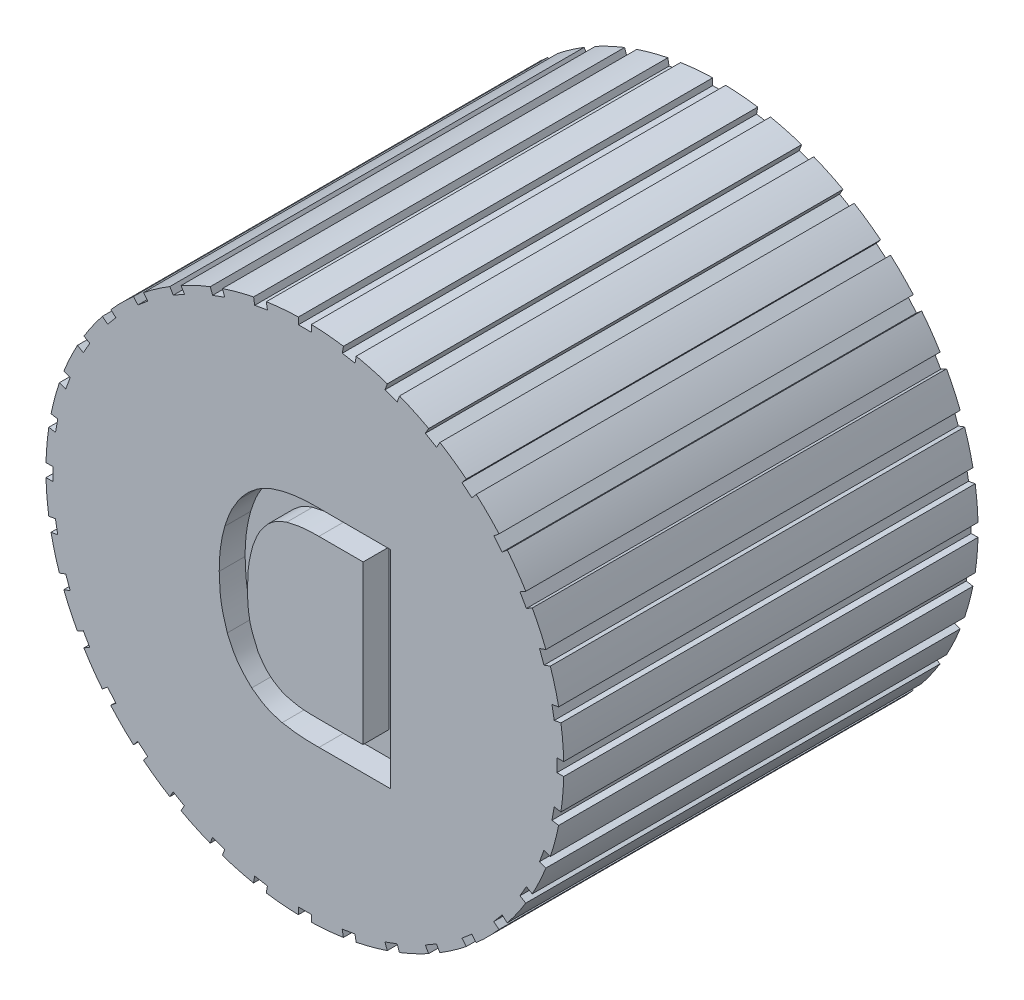
SolidWorks part; units mm, degrees
ref_plane "Front Plane" through (0, 0, 0) normal (0, 0, 1) x (1, 0, 0)
ref_plane "Top Plane" through (0, 0, 0) normal (0, 1, 0) x (1, 0, 0)
ref_plane "Right Plane" through (0, 0, 0) normal (1, 0, 0) x (0, 0, -1)
sketch "Sketch1" plane through (0, 0, 0) normal (0, 1, 0) x (1, 0, 0)
  line L0 (10, 0) -> (0, 0)
  line L1 (0, 0) -> (0, -16)
  line L2 (0, -16) -> (10, -16)
  line L3 (10, -16) -> (10, 0)
  line L4 (0, 0) -> (0, -16) construction
revolve "Revolve1" add sketch "Sketch1" angle 360 about L4
sketch "Sketch2" plane through (0, 0, 0) normal (0, 0, -1) x (-1, 0, 0)
  line L0 (3.183, 9.4799) -> (3.0936, 9.2344)
  line L1 (3.0936, 9.2344) -> (3.5632, 9.0635)
  line L2 (3.5632, 9.0635) -> (3.6526, 9.3091)
  arc A0 (3.6526, 9.3091) -> (3.183, 9.4799) centre (0, 0) ccw
extrude "Cut-Extrude1" cut sketch "Sketch2" against normal blind 16
sketch "Sketch3" plane through (0, 0, 0) normal (0, 0, -1) x (-1, 0, 0)
  line L0 (4.7808, 8.7832) -> (4.6502, 8.5569)
  line L1 (4.6502, 8.5569) -> (5.0829, 8.307)
  line L2 (5.0829, 8.307) -> (5.2136, 8.5334)
  arc A0 (5.2136, 8.5334) -> (4.7808, 8.7832) centre (0, 0) ccw
extrude "Cut-Extrude2" cut sketch "Sketch3" against normal blind 16
sketch "Sketch4" plane through (0, 0, 0) normal (0, 0, -1) x (-1, 0, 0)
  line L0 (6.2334, 7.8195) -> (6.0654, 7.6194)
  line L1 (6.0654, 7.6194) -> (6.4482, 7.2982)
  line L2 (6.4482, 7.2982) -> (6.6162, 7.4984)
  arc A0 (6.6162, 7.4984) -> (6.2334, 7.8195) centre (0, 0) ccw
extrude "Cut-Extrude3" cut sketch "Sketch4" against normal blind 16
sketch "Sketch5" plane through (0, 0, 0) normal (0, 0, -1) x (-1, 0, 0)
  line L0 (7.4965, 6.6183) -> (7.2963, 6.4504)
  line L1 (7.2963, 6.4504) -> (7.6176, 6.0676)
  line L2 (7.6176, 6.0676) -> (7.8178, 6.2356)
  arc A0 (7.8178, 6.2356) -> (7.4965, 6.6183) centre (0, 0) ccw
extrude "Cut-Extrude4" cut sketch "Sketch5" against normal blind 16
sketch "Sketch6" plane through (0, 0, 0) normal (0, 0, -1) x (-1, 0, 0)
  line L0 (8.5319, 5.216) -> (8.3056, 5.0854)
  line L1 (8.3056, 5.0854) -> (8.5554, 4.6526)
  line L2 (8.5554, 4.6526) -> (8.7818, 4.7833)
  arc A0 (8.7818, 4.7833) -> (8.5319, 5.216) centre (0, 0) ccw
extrude "Cut-Extrude5" cut sketch "Sketch6" against normal blind 16
sketch "Sketch7" plane through (0, 0, 0) normal (0, 0, -1) x (-1, 0, 0)
  line L0 (9.308, 3.6552) -> (9.0625, 3.5659)
  line L1 (9.0625, 3.5659) -> (9.2334, 3.0963)
  line L2 (9.2334, 3.0963) -> (9.479, 3.1857)
  arc A0 (9.479, 3.1857) -> (9.308, 3.6552) centre (0, 0) ccw
extrude "Cut-Extrude6" cut sketch "Sketch7" against normal blind 16
sketch "Sketch8" plane through (0, 0, 0) normal (0, 0, -1) x (-1, 0, 0)
  line L0 (9.8013, 1.9834) -> (9.544, 1.938)
  line L1 (9.544, 1.938) -> (9.6308, 1.4459)
  line L2 (9.6308, 1.4459) -> (9.8882, 1.4913)
  arc A0 (9.8882, 1.4913) -> (9.8013, 1.9834) centre (0, 0) ccw
extrude "Cut-Extrude7" cut sketch "Sketch8" against normal blind 16
sketch "Sketch9" plane through (0, 0, 0) normal (0, 0, -1) x (-1, 0, 0)
  line L0 (9.9968, 0.2513) -> (9.7356, 0.2513)
  line L1 (9.7356, 0.2513) -> (9.7356, -0.2484)
  line L2 (9.7356, -0.2484) -> (9.9969, -0.2484)
  arc A0 (9.9969, -0.2484) -> (9.9968, 0.2513) centre (0, 0) ccw
extrude "Cut-Extrude8" cut sketch "Sketch9" against normal blind 16
sketch "Sketch10" plane through (0, 0, 0) normal (0, 0, -1) x (-1, 0, 0)
  line L0 (9.8886, -1.4885) -> (9.6313, -1.4431)
  line L1 (9.6313, -1.4431) -> (9.5445, -1.9352)
  line L2 (9.5445, -1.9352) -> (9.8019, -1.9806)
  arc A0 (9.8019, -1.9806) -> (9.8886, -1.4885) centre (0, 0) ccw
extrude "Cut-Extrude9" cut sketch "Sketch10" against normal blind 16
sketch "Sketch11" plane through (0, 0, 0) normal (0, 0, -1) x (-1, 0, 0)
  line L0 (9.4799, -3.183) -> (9.2344, -3.0936)
  line L1 (9.2344, -3.0936) -> (9.0635, -3.5632)
  line L2 (9.0635, -3.5632) -> (9.3091, -3.6526)
  arc A0 (9.3091, -3.6526) -> (9.4799, -3.183) centre (0, 0) ccw
extrude "Cut-Extrude10" cut sketch "Sketch11" against normal blind 16
sketch "Sketch12" plane through (0, 0, 0) normal (0, 0, -1) x (-1, 0, 0)
  line L0 (8.7832, -4.7808) -> (8.5569, -4.6502)
  line L1 (8.5569, -4.6502) -> (8.307, -5.0829)
  line L2 (8.307, -5.0829) -> (8.5334, -5.2136)
  arc A0 (8.5334, -5.2136) -> (8.7832, -4.7808) centre (0, 0) ccw
extrude "Cut-Extrude11" cut sketch "Sketch12" against normal blind 16
sketch "Sketch13" plane through (0, 0, 0) normal (0, 0, -1) x (-1, 0, 0)
  line L0 (7.8195, -6.2334) -> (7.6194, -6.0654)
  line L1 (7.6194, -6.0654) -> (7.2982, -6.4482)
  line L2 (7.2982, -6.4482) -> (7.4984, -6.6162)
  arc A0 (7.4984, -6.6162) -> (7.8195, -6.2334) centre (0, 0) ccw
extrude "Cut-Extrude12" cut sketch "Sketch13" against normal blind 16
sketch "Sketch14" plane through (0, 0, 0) normal (0, 0, -1) x (-1, 0, 0)
  line L0 (6.6183, -7.4965) -> (6.4504, -7.2963)
  line L1 (6.4504, -7.2963) -> (6.0676, -7.6176)
  line L2 (6.0676, -7.6176) -> (6.2356, -7.8178)
  arc A0 (6.2356, -7.8178) -> (6.6183, -7.4965) centre (0, 0) ccw
extrude "Cut-Extrude13" cut sketch "Sketch14" against normal blind 16
sketch "Sketch15" plane through (0, 0, 0) normal (0, 0, -1) x (-1, 0, 0)
  line L0 (5.216, -8.5319) -> (5.0854, -8.3056)
  line L1 (5.0854, -8.3056) -> (4.6526, -8.5554)
  line L2 (4.6526, -8.5554) -> (4.7833, -8.7818)
  arc A0 (4.7833, -8.7818) -> (5.216, -8.5319) centre (0, 0) ccw
extrude "Cut-Extrude14" cut sketch "Sketch15" against normal blind 16
sketch "Sketch16" plane through (0, 0, 0) normal (0, 0, -1) x (-1, 0, 0)
  line L0 (3.6552, -9.308) -> (3.5659, -9.0625)
  line L1 (3.5659, -9.0625) -> (3.0963, -9.2334)
  line L2 (3.0963, -9.2334) -> (3.1857, -9.479)
  arc A0 (3.1857, -9.479) -> (3.6552, -9.308) centre (0, 0) ccw
extrude "Cut-Extrude15" cut sketch "Sketch16" against normal blind 16
sketch "Sketch17" plane through (0, 0, 0) normal (0, 0, -1) x (-1, 0, 0)
  line L0 (1.9834, -9.8013) -> (1.938, -9.544)
  line L1 (1.938, -9.544) -> (1.4459, -9.6308)
  line L2 (1.4459, -9.6308) -> (1.4913, -9.8882)
  arc A0 (1.4913, -9.8882) -> (1.9834, -9.8013) centre (0, 0) ccw
extrude "Cut-Extrude16" cut sketch "Sketch17" against normal blind 16
sketch "Sketch18" plane through (0, 0, 0) normal (0, 0, -1) x (-1, 0, 0)
  line L0 (0.2513, -9.9968) -> (0.2513, -9.7356)
  line L1 (0.2513, -9.7356) -> (-0.2484, -9.7356)
  line L2 (-0.2484, -9.7356) -> (-0.2484, -9.9969)
  arc A0 (-0.2484, -9.9969) -> (0.2513, -9.9968) centre (0, 0) ccw
extrude "Cut-Extrude17" cut sketch "Sketch18" against normal blind 16
sketch "Sketch19" plane through (0, 0, 0) normal (0, 0, -1) x (-1, 0, 0)
  line L0 (-1.4885, -9.8886) -> (-1.4431, -9.6313)
  line L1 (-1.4431, -9.6313) -> (-1.9352, -9.5445)
  line L2 (-1.9352, -9.5445) -> (-1.9806, -9.8019)
  arc A0 (-1.9806, -9.8019) -> (-1.4885, -9.8886) centre (0, 0) ccw
extrude "Cut-Extrude18" cut sketch "Sketch19" against normal blind 16
sketch "Sketch20" plane through (0, 0, 0) normal (0, 0, -1) x (-1, 0, 0)
  line L0 (-3.183, -9.4799) -> (-3.0936, -9.2344)
  line L1 (-3.0936, -9.2344) -> (-3.5632, -9.0635)
  line L2 (-3.5632, -9.0635) -> (-3.6526, -9.3091)
  arc A0 (-3.6526, -9.3091) -> (-3.183, -9.4799) centre (0, 0) ccw
extrude "Cut-Extrude19" cut sketch "Sketch20" against normal blind 16
sketch "Sketch21" plane through (0, 0, 0) normal (0, 0, -1) x (-1, 0, 0)
  line L0 (-4.7808, -8.7832) -> (-4.6502, -8.5569)
  line L1 (-4.6502, -8.5569) -> (-5.0829, -8.307)
  line L2 (-5.0829, -8.307) -> (-5.2136, -8.5334)
  arc A0 (-5.2136, -8.5334) -> (-4.7808, -8.7832) centre (0, 0) ccw
extrude "Cut-Extrude20" cut sketch "Sketch21" against normal blind 16
sketch "Sketch22" plane through (0, 0, 0) normal (0, 0, -1) x (-1, 0, 0)
  line L0 (-6.2334, -7.8195) -> (-6.0654, -7.6194)
  line L1 (-6.0654, -7.6194) -> (-6.4482, -7.2982)
  line L2 (-6.4482, -7.2982) -> (-6.6162, -7.4984)
  arc A0 (-6.6162, -7.4984) -> (-6.2334, -7.8195) centre (0, 0) ccw
extrude "Cut-Extrude21" cut sketch "Sketch22" against normal blind 16
sketch "Sketch23" plane through (0, 0, 0) normal (0, 0, -1) x (-1, 0, 0)
  line L0 (-7.4965, -6.6183) -> (-7.2963, -6.4504)
  line L1 (-7.2963, -6.4504) -> (-7.6176, -6.0676)
  line L2 (-7.6176, -6.0676) -> (-7.8178, -6.2356)
  arc A0 (-7.8178, -6.2356) -> (-7.4965, -6.6183) centre (0, 0) ccw
extrude "Cut-Extrude22" cut sketch "Sketch23" against normal blind 16
sketch "Sketch24" plane through (0, 0, 0) normal (0, 0, -1) x (-1, 0, 0)
  line L0 (-8.5319, -5.216) -> (-8.3056, -5.0854)
  line L1 (-8.3056, -5.0854) -> (-8.5554, -4.6526)
  line L2 (-8.5554, -4.6526) -> (-8.7818, -4.7833)
  arc A0 (-8.7818, -4.7833) -> (-8.5319, -5.216) centre (0, 0) ccw
extrude "Cut-Extrude23" cut sketch "Sketch24" against normal blind 16
sketch "Sketch25" plane through (0, 0, 0) normal (0, 0, -1) x (-1, 0, 0)
  line L0 (-9.308, -3.6552) -> (-9.0625, -3.5659)
  line L1 (-9.0625, -3.5659) -> (-9.2334, -3.0963)
  line L2 (-9.2334, -3.0963) -> (-9.479, -3.1857)
  arc A0 (-9.479, -3.1857) -> (-9.308, -3.6552) centre (0, 0) ccw
extrude "Cut-Extrude24" cut sketch "Sketch25" against normal blind 16
sketch "Sketch26" plane through (0, 0, 0) normal (0, 0, -1) x (-1, 0, 0)
  line L0 (-9.8013, -1.9834) -> (-9.544, -1.938)
  line L1 (-9.544, -1.938) -> (-9.6308, -1.4459)
  line L2 (-9.6308, -1.4459) -> (-9.8882, -1.4913)
  arc A0 (-9.8882, -1.4913) -> (-9.8013, -1.9834) centre (0, 0) ccw
extrude "Cut-Extrude25" cut sketch "Sketch26" against normal blind 16
sketch "Sketch27" plane through (0, 0, 0) normal (0, 0, -1) x (-1, 0, 0)
  line L0 (-9.9968, -0.2513) -> (-9.7356, -0.2513)
  line L1 (-9.7356, -0.2513) -> (-9.7356, 0.2484)
  line L2 (-9.7356, 0.2484) -> (-9.9969, 0.2484)
  arc A0 (-9.9969, 0.2484) -> (-9.9968, -0.2513) centre (0, 0) ccw
extrude "Cut-Extrude26" cut sketch "Sketch27" against normal blind 16
sketch "Sketch28" plane through (0, 0, 0) normal (0, 0, -1) x (-1, 0, 0)
  line L0 (-9.8886, 1.4885) -> (-9.6313, 1.4431)
  line L1 (-9.6313, 1.4431) -> (-9.5445, 1.9352)
  line L2 (-9.5445, 1.9352) -> (-9.8019, 1.9806)
  arc A0 (-9.8019, 1.9806) -> (-9.8886, 1.4885) centre (0, 0) ccw
extrude "Cut-Extrude27" cut sketch "Sketch28" against normal blind 16
sketch "Sketch29" plane through (0, 0, 0) normal (0, 0, -1) x (-1, 0, 0)
  line L0 (-9.4799, 3.183) -> (-9.2344, 3.0936)
  line L1 (-9.2344, 3.0936) -> (-9.0635, 3.5632)
  line L2 (-9.0635, 3.5632) -> (-9.3091, 3.6526)
  arc A0 (-9.3091, 3.6526) -> (-9.4799, 3.183) centre (0, 0) ccw
extrude "Cut-Extrude28" cut sketch "Sketch29" against normal blind 16
sketch "Sketch30" plane through (0, 0, 0) normal (0, 0, -1) x (-1, 0, 0)
  line L0 (-8.7832, 4.7808) -> (-8.5569, 4.6502)
  line L1 (-8.5569, 4.6502) -> (-8.307, 5.0829)
  line L2 (-8.307, 5.0829) -> (-8.5334, 5.2136)
  arc A0 (-8.5334, 5.2136) -> (-8.7832, 4.7808) centre (0, 0) ccw
extrude "Cut-Extrude29" cut sketch "Sketch30" against normal blind 16
sketch "Sketch31" plane through (0, 0, 0) normal (0, 0, -1) x (-1, 0, 0)
  line L0 (-7.8195, 6.2334) -> (-7.6194, 6.0654)
  line L1 (-7.6194, 6.0654) -> (-7.2982, 6.4482)
  line L2 (-7.2982, 6.4482) -> (-7.4984, 6.6162)
  arc A0 (-7.4984, 6.6162) -> (-7.8195, 6.2334) centre (0, 0) ccw
extrude "Cut-Extrude30" cut sketch "Sketch31" against normal blind 16
sketch "Sketch32" plane through (0, 0, 0) normal (0, 0, -1) x (-1, 0, 0)
  line L0 (-6.6183, 7.4965) -> (-6.4504, 7.2963)
  line L1 (-6.4504, 7.2963) -> (-6.0676, 7.6176)
  line L2 (-6.0676, 7.6176) -> (-6.2356, 7.8178)
  arc A0 (-6.2356, 7.8178) -> (-6.6183, 7.4965) centre (0, 0) ccw
extrude "Cut-Extrude31" cut sketch "Sketch32" against normal blind 16
sketch "Sketch33" plane through (0, 0, 0) normal (0, 0, -1) x (-1, 0, 0)
  line L0 (-5.216, 8.5319) -> (-5.0854, 8.3056)
  line L1 (-5.0854, 8.3056) -> (-4.6526, 8.5554)
  line L2 (-4.6526, 8.5554) -> (-4.7833, 8.7818)
  arc A0 (-4.7833, 8.7818) -> (-5.216, 8.5319) centre (0, 0) ccw
extrude "Cut-Extrude32" cut sketch "Sketch33" against normal blind 16
sketch "Sketch34" plane through (0, 0, 0) normal (0, 0, -1) x (-1, 0, 0)
  line L0 (-3.6552, 9.308) -> (-3.5659, 9.0625)
  line L1 (-3.5659, 9.0625) -> (-3.0963, 9.2334)
  line L2 (-3.0963, 9.2334) -> (-3.1857, 9.479)
  arc A0 (-3.1857, 9.479) -> (-3.6552, 9.308) centre (0, 0) ccw
extrude "Cut-Extrude33" cut sketch "Sketch34" against normal blind 16
sketch "Sketch35" plane through (0, 0, 0) normal (0, 0, -1) x (-1, 0, 0)
  line L0 (-1.9834, 9.8013) -> (-1.938, 9.544)
  line L1 (-1.938, 9.544) -> (-1.4459, 9.6308)
  line L2 (-1.4459, 9.6308) -> (-1.4913, 9.8882)
  arc A0 (-1.4913, 9.8882) -> (-1.9834, 9.8013) centre (0, 0) ccw
extrude "Cut-Extrude34" cut sketch "Sketch35" against normal blind 16
sketch "Sketch36" plane through (0, 0, 0) normal (0, 0, -1) x (-1, 0, 0)
  line L0 (-0.2513, 9.9968) -> (-0.2513, 9.7356)
  line L1 (-0.2513, 9.7356) -> (0.2484, 9.7356)
  line L2 (0.2484, 9.7356) -> (0.2484, 9.9969)
  arc A0 (0.2484, 9.9969) -> (-0.2513, 9.9968) centre (0, 0) ccw
extrude "Cut-Extrude35" cut sketch "Sketch36" against normal blind 16
sketch "Sketch37" plane through (0, 0, 0) normal (0, 0, -1) x (-1, 0, 0)
  line L0 (1.4885, 9.8886) -> (1.4431, 9.6313)
  line L1 (1.4431, 9.6313) -> (1.9352, 9.5445)
  line L2 (1.9352, 9.5445) -> (1.9806, 9.8019)
  arc A0 (1.9806, 9.8019) -> (1.4885, 9.8886) centre (0, 0) ccw
extrude "Cut-Extrude36" cut sketch "Sketch37" against normal blind 16
ref_plane "Plane1" through (0, 0, 13) normal (0, 0, 1) x (1, 0, 0)
sketch "Sketch38" plane through (0, 0, 13) normal (0, 0, 1) x (1, 0, 0)
  line L0 (3.3034, -4.003) -> (0.5476, -4.0005)
  line L1 (0.4238, 3.9996) -> (3.3105, 3.997)
  line L2 (3.3105, 3.997) -> (3.3034, -4.003)
  arc A0 (0.5476, -4.0005) -> (-0.8766, -3.8846) centre (0.3773, 2.7169) cw
  arc A1 (-3.307, -0.0407) -> (-3.0927, 1.5744) centre (2.2817, 0.0396) cw
  arc A2 (-0.8615, 3.8643) -> (0.4238, 3.9996) centre (0.3478, -1.4518) cw
  spline S0 degree 3 poles (-0.8766, -3.8846) (-0.9235, -3.8714) (-1.0172, -3.8449) (-1.1571, -3.8029) (-1.2954, -3.756) (-1.4314, -3.702) (-1.5633, -3.6381) (-1.6899, -3.5641) (-1.8122, -3.4833) (-1.9316, -3.398) (-2.0101, -3.3397) (-2.0494, -3.3106) knots 0 0 0 0 0.110943 0.2218 0.332579 0.443493 0.554813 0.665987 0.777299 0.888646 1 1 1 1
  spline S1 degree 3 poles (-2.0494, -3.3106) (-2.1297, -3.2323) (-2.2903, -3.0759) (-2.517, -2.8273) (-2.7077, -2.5497) (-2.86, -2.2502) (-2.9499, -2.0453) (-2.9949, -1.9427) knots 0 0 0 0 0.200524 0.4005 0.600168 0.799889 1 1 1 1
  spline S2 degree 3 poles (-2.9949, -1.9427) (-3.0161, -1.8743) (-3.0584, -1.7374) (-3.119, -1.5313) (-3.1739, -1.3235) (-3.2202, -1.1134) (-3.2542, -0.9008) (-3.277, -0.6865) (-3.2915, -0.4715) (-3.3006, -0.2561) (-3.3049, -0.1125) (-3.307, -0.0407) knots 0 0 0 0 0.110984 0.221911 0.332787 0.443747 0.554989 0.666185 0.777445 0.888721 1 1 1 1
  spline S3 degree 3 poles (-3.0927, 1.5744) (-3.0777, 1.6199) (-3.0477, 1.7109) (-3.0012, 1.8469) (-2.9517, 1.9817) (-2.8975, 2.1148) (-2.8371, 2.2452) (-2.7698, 2.3719) (-2.6979, 2.4958) (-2.6227, 2.6179) (-2.5716, 2.6986) (-2.546, 2.739) knots 0 0 0 0 0.111256 0.222509 0.333749 0.444938 0.556161 0.667141 0.778048 0.888999 1 1 1 1
  spline S4 degree 3 poles (-2.546, 2.739) (-2.5226, 2.7693) (-2.4758, 2.83) (-2.4045, 2.9202) (-2.3309, 3.0085) (-2.2541, 3.0941) (-2.1729, 3.1754) (-2.0873, 3.2518) (-1.9988, 3.3246) (-1.9083, 3.395) (-1.8473, 3.4411) (-1.8168, 3.4641) knots 0 0 0 0 0.111275 0.222546 0.333801 0.444995 0.556234 0.667198 0.77808 0.889012 1 1 1 1
  spline S5 degree 3 poles (-1.8168, 3.4641) (-1.7835, 3.4836) (-1.7169, 3.5226) (-1.6163, 3.5798) (-1.5142, 3.6342) (-1.4099, 3.6844) (-1.303, 3.7286) (-1.1941, 3.7673) (-1.0839, 3.8019) (-0.9729, 3.8338) (-0.8986, 3.8542) (-0.8615, 3.8643) knots 0 0 0 0 0.111234 0.222464 0.333676 0.444816 0.556033 0.667043 0.777987 0.888971 1 1 1 1
extrude "Cut-Extrude37" cut sketch "Sketch38" against normal blind 1 from surface at 3 starting at face at (0, 0, 16)
ref_plane "Plane2" through (0, 0, 18) normal (0, 0, -1) x (0, 1, 0)
sketch "Sketch39" plane through (0, 0, 18) normal (0, 0, -1) x (0, 1, 0)
  line L0 (-3.0564, 0.5648) -> (-3.058, 2.2456)
  line L1 (-3.058, 2.2456) -> (3.0539, 2.251)
  line L2 (3.0539, 2.251) -> (3.0554, 0.543)
  spline S0 degree 3 poles (-1.9875, -1.8053) (-2.0296, -1.7768) (-2.114, -1.7196) (-2.2386, -1.6313) (-2.3587, -1.5378) (-2.4717, -1.4367) (-2.5744, -1.3255) (-2.6647, -1.2034) (-2.7458, -1.0741) (-2.8203, -0.9403) (-2.8678, -0.85) (-2.8915, -0.8048) knots 0 0 0 0 0.11148 0.22295 0.334208 0.444557 0.554462 0.664972 0.776569 0.888273 1 1 1 1
  spline S1 degree 3 poles (-2.8915, -0.8048) (-2.9043, -0.7551) (-2.9299, -0.6556) (-2.9658, -0.5059) (-2.9973, -0.3552) (-3.0227, -0.2032) (-3.0392, -0.0501) (-3.0491, 0.1034) (-3.0542, 0.2572) (-3.0561, 0.411) (-3.0563, 0.5135) (-3.0564, 0.5648) knots 0 0 0 0 0.111189 0.222372 0.33354 0.444632 0.555822 0.66688 0.777891 0.888929 1 1 1 1
  spline S2 degree 3 poles (3.0554, 0.543) (3.055, 0.4965) (3.0542, 0.4034) (3.0516, 0.2639) (3.0463, 0.1245) (3.0368, -0.0147) (3.0217, -0.1534) (2.9994, -0.2909) (2.9722, -0.4274) (2.9416, -0.5632) (2.92, -0.6535) (2.9092, -0.6986) knots 0 0 0 0 0.111247 0.222492 0.333727 0.444924 0.556136 0.66712 0.778037 0.888994 1 1 1 1
  spline S3 degree 3 poles (2.9092, -0.6986) (2.8986, -0.7278) (2.8772, -0.786) (2.8439, -0.873) (2.8077, -0.9587) (2.7673, -1.0426) (2.7214, -1.1234) (2.6694, -1.2003) (2.6135, -1.2741) (2.555, -1.3459) (2.5151, -1.393) (2.4951, -1.4166) knots 0 0 0 0 0.1114 0.222795 0.334161 0.44542 0.556756 0.667609 0.778316 0.889109 1 1 1 1
  spline S4 degree 3 poles (2.4951, -1.4166) (2.4618, -1.4449) (2.3951, -1.5016) (2.2935, -1.5848) (2.189, -1.6642) (2.0803, -1.7378) (1.9663, -1.8029) (1.8484, -1.86) (1.728, -1.9112) (1.6061, -1.9586) (1.5243, -1.989) (1.4834, -2.0041) knots 0 0 0 0 0.111317 0.222627 0.333904 0.445048 0.556342 0.667291 0.778124 0.889025 1 1 1 1
  spline S5 degree 3 poles (1.4834, -2.0041) (1.4274, -2.0189) (1.3154, -2.0483) (1.147, -2.0904) (0.9775, -2.1282) (0.8067, -2.1597) (0.6346, -2.1823) (0.4617, -2.1971) (0.2886, -2.2064) (0.1153, -2.2119) (-0.0002, -2.2144) (-0.058, -2.2156) knots 0 0 0 0 0.111203 0.222402 0.333586 0.44471 0.555903 0.666942 0.777929 0.888948 1 1 1 1
  spline S6 degree 3 poles (-0.058, -2.2156) (-0.1907, -2.2132) (-0.4559, -2.2085) (-0.8534, -2.18) (-1.2459, -2.1032) (-1.6221, -1.9669) (-1.8656, -1.8592) (-1.9875, -1.8053) knots 0 0 0 0 0.19971 0.399178 0.59927 0.799339 1 1 1 1
extrude "Boss-Extrude1" add sketch "Sketch39" against normal blind 1 from surface at 3 starting at face at (-0.8438, 0.461, 15)
hole_wizard "Ø6.0 (6) Diameter Hole1" positions "Sketch41" profile "Sketch40" hole size "Ø6.0" standard "ANSI Metric"
sketch "Sketch41" plane through (0, 0, 0) normal (0, 0, -1) x (-1, 0, 0)
  point P0 (0, 0)
sketch "Sketch40" plane through (0, 0, 0) normal (1, 0, 0) x (0, 1, 0)
  line L0 (0, 0) -> (0, 14)
  line L1 (0, 14) -> (3, 14)
  line L2 (3, 14) -> (3, 0)
  line L5 (3, 0) -> (0, 0)
  line L10 (0, 14) -> (-3, 14) construction
  line L11 (0, -6.35) -> (0, 107.95) construction
  dimension "Hole Dia." = 6
  dimension "Hole Depth" = 14
  dimension "Drill Angle" = 180
